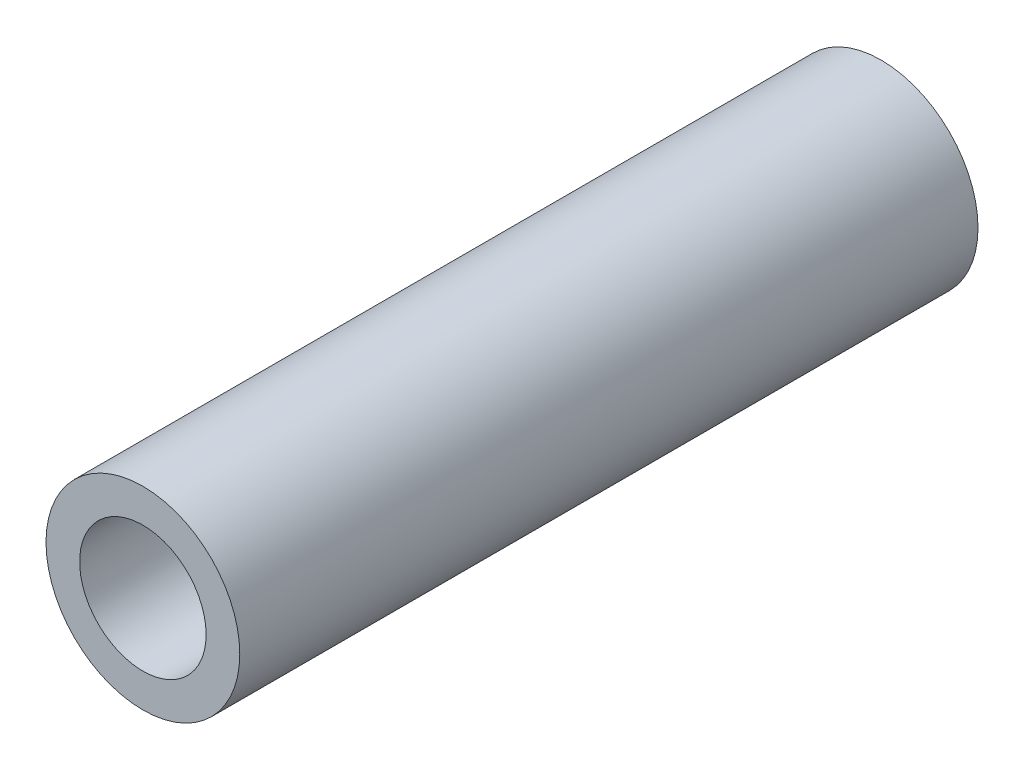
SolidWorks part; units mm, degrees
ref_plane "Front Plane" through (0, 0, 0) normal (0, 0, 1) x (1, 0, 0)
ref_plane "Top Plane" through (0, 0, 0) normal (0, 1, 0) x (1, 0, 0)
ref_plane "Right Plane" through (0, 0, 0) normal (1, 0, 0) x (0, 0, -1)
sketch "Sketch1" plane through (0, 0, 0) normal (0, 0, 1) x (1, 0, 0)
  circle A0 centre (0, 0) radius 2.5
  dimension "D1" = 5
extrude "Boss-Extrude1" add sketch "Sketch1" along normal blind 19.05
hole_wizard "#4 Clearance Hole1" positions "Sketch6" profile "Sketch5" hole size "#4" standard "ANSI Inch" end condition through all
sketch "Sketch6" plane through (0, 0, 19.05) normal (0, 0, 1) x (1, 0, 0)
  point P0 (0, 0)
sketch "Sketch5" plane through (0, 0, 19.05) normal (1, 0, 0) x (0, -1, 0)
  line L0 (0, 0) -> (0, 19.05)
  line L1 (0, 19.05) -> (1.6319, 19.05)
  line L2 (1.6319, 19.05) -> (1.6319, 0)
  line L5 (1.6319, 0) -> (0, 0)
  line L11 (0, -6.35) -> (0, 107.95) construction
  dimension "Thru Hole Dia." = 3.2639
  dimension "Thru Hole Depth" = 19.05
